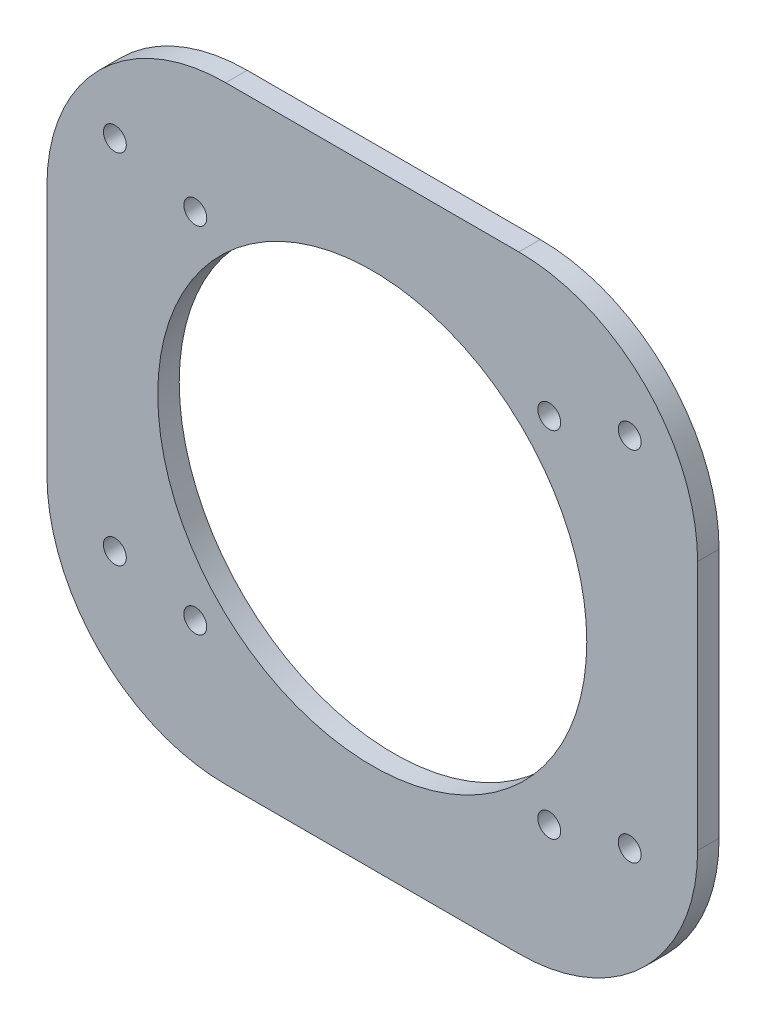
SolidWorks part; units mm, degrees
ref_plane "前视基准面" through (0, 0, 0) normal (0, 0, 1) x (1, 0, 0)
ref_plane "上视基准面" through (0, 0, 0) normal (0, 1, 0) x (1, 0, 0)
ref_plane "右视基准面" through (0, 0, 0) normal (1, 0, 0) x (0, 0, -1)
sketch "草图1" plane through (0, 0, 0) normal (0, 0, 1) x (1, 0, 0)
  line L0 (0, 25) -> (0, -25) construction
  line L1 (-36, 25) -> (36, 25) construction
  line L2 (-36, 25) -> (-36, -25) construction
  line L3 (-36, -25) -> (36, -25) construction
  line L4 (36, 25) -> (36, -25) construction
  line L5 (-36, 25) -> (36, -25) construction
  line L6 (-36, -25) -> (36, 25) construction
  line L7 (-25, 25) -> (-25, -25) construction
  line L8 (-25, 25) -> (25, 25) construction
  line L9 (-25, 25) -> (-25, -25) construction
  line L10 (-25, -25) -> (25, -25) construction
  line L11 (25, 25) -> (25, -25) construction
  line L12 (-25, 25) -> (25, -25) construction
  line L13 (-25, -25) -> (25, 25) construction
  line L14 (-36, 25) -> (-36, -25) construction
  line L16 (-45.5, 37) -> (45.5, 37)
  line L17 (-45.5, 37) -> (-45.5, -37)
  line L18 (-45.5, -37) -> (45.5, -37)
  line L19 (45.5, 37) -> (45.5, -37)
  line L20 (-45.5, 37) -> (45.5, -37) construction
  line L21 (-45.5, -37) -> (45.5, 37) construction
  circle A0 centre (36, -25) radius 1.6
  circle A1 centre (36, 25) radius 1.6
  circle A6 centre (-36, 25) radius 1.6
  circle A7 centre (-36, -25) radius 1.6
  point P0 (0, 0)
  point P10 (0, 0)
  point P21 (0, 0)
  dimension "D1" = 72
  dimension "D3" = 3.2
  dimension "D4" = 3.2
  dimension "D2" = 50
  dimension "D5" = 50
  dimension "D6" = 50
  dimension "D9" = 91
  dimension "D10" = 74
extrude "凸台-拉伸1" add sketch "草图1" along normal blind 3
sketch "草图2" plane through (0, 0, 3) normal (0, 0, 1) x (1, 0, 0)
  line L0 (0, 37) -> (0, -37) construction
  line L1 (45.5, 37) -> (-45.5, 37) construction
  line L2 (-45.5, -37) -> (45.5, -37) construction
  line L4 (-24.7487, 21.7487) -> (24.7487, 21.7487) construction
  line L5 (-24.7487, 21.7487) -> (-24.7487, -27.7487) construction
  line L6 (-24.7487, -27.7487) -> (24.7487, -27.7487) construction
  line L7 (24.7487, 21.7487) -> (24.7487, -27.7487) construction
  line L8 (-24.7487, 21.7487) -> (24.7487, -27.7487) construction
  line L9 (-24.7487, -27.7487) -> (24.7487, 21.7487) construction
  circle A0 centre (0, -3) radius 30
  circle A1 centre (24.7487, -27.7487) radius 1.6
  circle A2 centre (24.7487, 21.7487) radius 1.6
  circle A3 centre (-24.7487, -27.7487) radius 1.6
  circle A4 centre (-24.7487, 21.7487) radius 1.6
  circle A5 centre (0, -3) radius 35 construction
  dimension "D1" = 60
  dimension "D5" = 3.2
  dimension "D6" = 3.2
  dimension "D3" = 70
  dimension "D4" = 24.7487
  dimension "D2" = 3
extrude "切除-拉伸1" cut sketch "草图2" against normal blind 10
sketch "草图3" plane through (0, 0, 3) normal (0, 0, 1) x (1, 0, 0)
  line L0 (45.5, -37) -> (45.5, 37) construction
  line L1 (-45.5, 37) -> (45.5, 37)
  line L2 (-45.5, 37) -> (-45.5, 31)
  line L3 (-45.5, 31) -> (45.5, 31)
  line L4 (45.5, 37) -> (45.5, 31)
  dimension "D1" = 6
extrude "切除-拉伸2" cut sketch "草图3" against normal blind 10
sketch "草图4" plane through (0, 0, 3) normal (0, 0, 1) x (1, 0, 0)
  line L0 (45.5, -37) -> (45.5, 31) construction
  line L1 (-45.5, -37) -> (45.5, -37)
  line L2 (-45.5, -37) -> (-45.5, -45.5)
  line L3 (-45.5, -45.5) -> (45.5, -45.5)
  line L4 (45.5, -37) -> (45.5, -45.5)
  line L5 (-45.5, 0) -> (0, 0) construction
  line L6 (-45.5, 31) -> (-45.5, -37) construction
  line L12 (-45.5, 45.5) -> (45.5, 45.5)
  line L13 (-45.5, 45.5) -> (-45.5, 31)
  line L14 (-45.5, 31) -> (45.5, 31)
  line L15 (45.5, 45.5) -> (45.5, 31)
  dimension "D1" = 0
  dimension "D2" = 45.5
extrude "凸台-拉伸2" add sketch "草图4" against normal blind 3
sketch "草图5" plane through (0, 0, 3) normal (0, 0, 1) x (1, 0, 0)
  line L0 (45.5, -45.5) -> (45.5, 45.5) construction
  line L1 (-45.5, 45.5) -> (45.5, 45.5)
  line L2 (-45.5, 45.5) -> (-45.5, 39.5)
  line L3 (-45.5, 39.5) -> (45.5, 39.5)
  line L4 (45.5, 45.5) -> (45.5, 39.5)
  dimension "D1" = 6
extrude "切除-拉伸3" cut sketch "草图5" against normal blind 3
fillet "圆角4" radius 25 4 edges at (45.5, -45.5, 1.5) (45.5, 39.5, 1.5) (-45.5, 39.5, 1.5) (-45.5, -45.5, 1.5)
